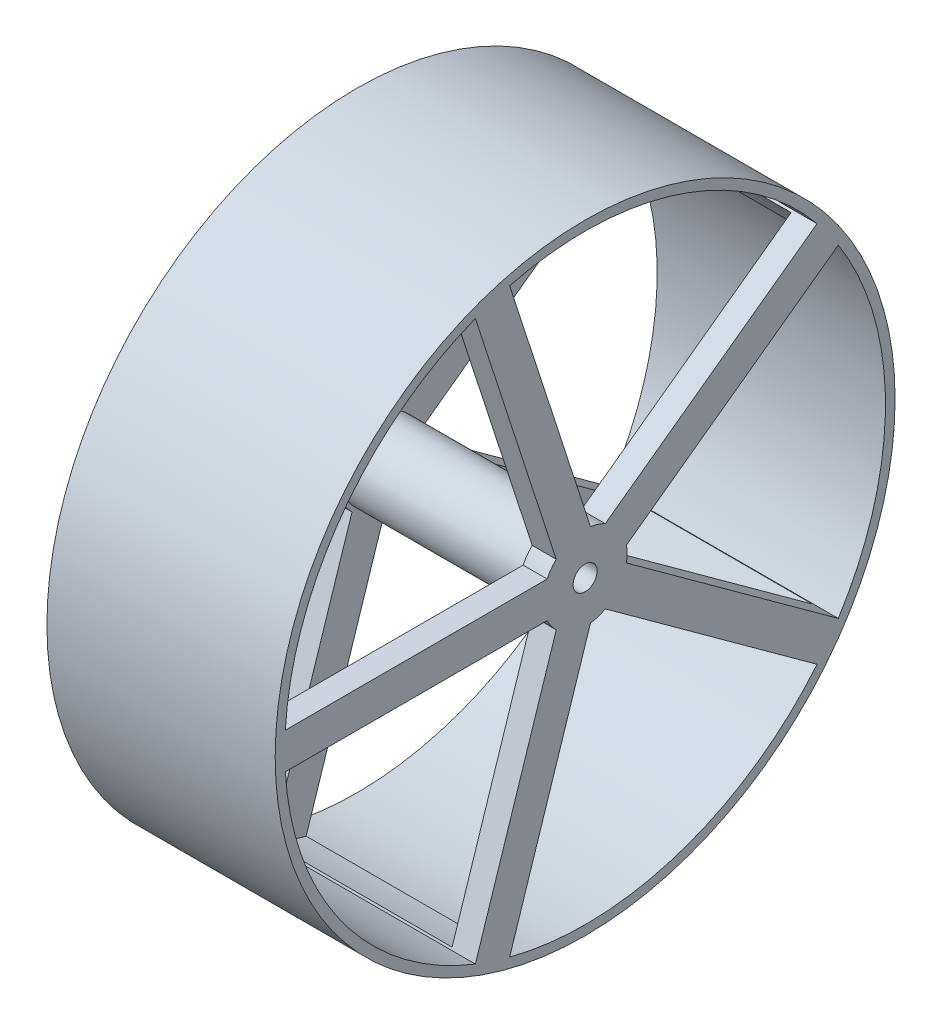
SolidWorks part; units mm, degrees
material "PE Low Density Film"
ref_plane "Front Plane" through (0, 0, 0) normal (1, 0, 0) x (0, 1, 0)
ref_plane "Top Plane" through (0, 0, 0) normal (0, 0, 1) x (0, 1, 0)
ref_plane "Right Plane" through (0, 0, 0) normal (0, 1, 0) x (-1, 0, 0)
sketch "Sketch2" plane through (0, 0, 0) normal (1, 0, 0) x (0, 1, 0)
  line L0 (0, -1000) -> (0, 0) construction
  line L8 (-7.5, 15.8114) -> (-7.5, 124.7748)
  line L10 (7.5, 15.8114) -> (7.5, 124.7748)
  line L11 (12.7199, 12.0189) -> (116.3503, 45.6905)
  line L13 (17.3552, -2.2469) -> (120.9855, 31.4246)
  line L15 (15.3613, -8.3833) -> (79.4084, -96.5365)
  line L17 (3.2261, -17.2001) -> (67.2732, -105.3533)
  line L19 (-3.2261, -17.2001) -> (-67.2732, -105.3533)
  line L21 (-15.3613, -8.3833) -> (-79.4084, -96.5365)
  line L23 (-17.3552, -2.2469) -> (-120.9855, 31.4246)
  line L25 (-12.7199, 12.0189) -> (-116.3503, 45.6905)
  line L31 (-962.4087, -312.7056) -> (0, 0) construction
  circle A0 centre (0, 0) radius 5
  circle A7 centre (0, 0) radius 17.5
  arc A8 (-120.9855, 31.4246) -> (-79.4084, -96.5365) centre (0, 0) ccw
  circle A9 centre (0, 0) radius 129
  circle A10 centre (0, 0) radius 125 construction
  arc A11 (-67.2732, -105.3533) -> (67.2732, -105.3533) centre (0, 0) ccw
  arc A12 (79.4084, -96.5365) -> (120.9855, 31.4246) centre (0, 0) ccw
  arc A13 (116.3503, 45.6905) -> (7.5, 124.7748) centre (0, 0) ccw
  arc A14 (-7.5, 124.7748) -> (-116.3503, 45.6905) centre (0, 0) ccw
  point P17 (0, 0)
  point P24 (0, 0)
  point P27 (0, 0)
  point P28 (0, 0)
  point P40 (0, 0)
  dimension "D1" = 10
  dimension "D2" = 35
  dimension "D7" = 4
  dimension "D4" = 125
  dimension "D3" = 15
  dimension "D5" = 5
extrude "Boss-Extrude1" add sketch "Sketch2" along normal mid plane 95
sketch "Sketch3" plane through (0, 0, 0) normal (0, 1, 0) x (-1, 0, 0)
  line L3 (47.5, 129) -> (-47.5, 129) construction
  line L7 (37.5, 129) -> (-37.5, 129) construction
  line L9 (-37.5, 124) -> (-37.5, 15.8114)
  line L12 (-47.5, 15.8114) -> (47.5, 15.8114) construction
  line L13 (-37.5, 15.8114) -> (37.5, 15.8114)
  line L15 (0, -1000) -> (0, 49000) construction
  line L16 (-37.5, 119) -> (-37.5, -119) construction
  line L17 (37.5, -119) -> (37.5, 119) construction
  line L18 (47.5, 129) -> (-47.5, 129) construction
  line L19 (-47.5, -129) -> (47.5, -129) construction
  line L20 (37.5, 124) -> (-37.5, 124)
  line L22 (37.5, 119) -> (-37.5, 119) construction
  line L23 (-37.5, -119) -> (37.5, -119) construction
  line L24 (-1000, 0) -> (47.5, 0) construction
  line L25 (-47.5, 129) -> (-47.5, -129) construction
  line L27 (37.5, 15.8114) -> (37.5, 124)
  line L28 (47.5, -129) -> (47.5, 129) construction
  dimension "D1" = 10
  dimension "D2" = 5
revolve "Cut-Revolve1" cut sketch "Sketch3" angle 360 about L24
